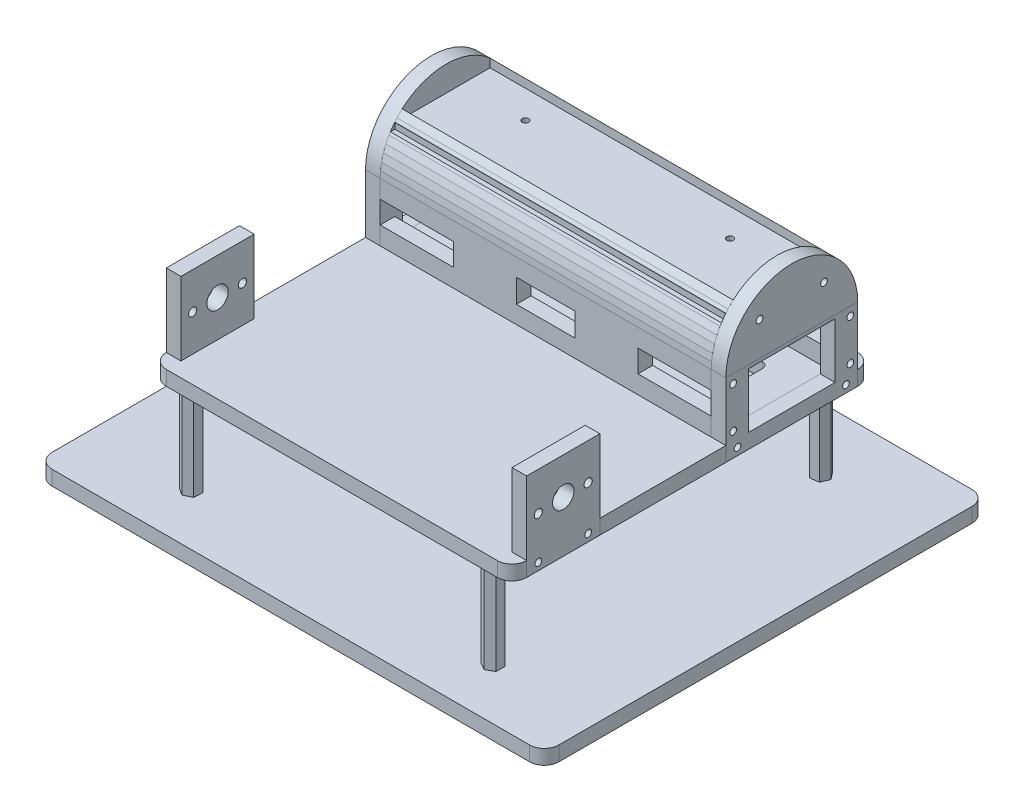
SolidWorks part; units mm, degrees
material "ABS"
ref_plane "Plano frontal" through (0, 0, 0) normal (0, 0, 1) x (1, 0, 0)
ref_plane "Plano superior" through (0, 0, 0) normal (0, 1, 0) x (1, 0, 0)
ref_plane "Plano direito" through (0, 0, 0) normal (1, 0, 0) x (0, 0, -1)
sketch "Esboço1" plane through (0, 0, 0) normal (0, 1, 0) x (1, 0, 0)
  line L1 (-20.6889, 116.4867) -> (92.3111, 116.4867)
  line L2 (-25.6889, 111.4867) -> (-25.6889, -1.5133)
  line L3 (-20.6889, -6.5133) -> (92.3111, -6.5133)
  line L4 (97.3111, 111.4867) -> (97.3111, -1.5133)
  arc A0 (92.3111, -6.5133) -> (97.3111, -1.5133) centre (92.3111, -1.5133) ccw
  arc A1 (-20.6889, -6.5133) -> (-25.6889, -1.5133) centre (-20.6889, -1.5133) cw
  arc A2 (97.3111, 111.4867) -> (92.3111, 116.4867) centre (92.3111, 111.4867) ccw
  arc A3 (-25.6889, 111.4867) -> (-20.6889, 116.4867) centre (-20.6889, 111.4867) cw
  dimension "D1" = 5
extrude "Ressalto-extrusão1" add sketch "Esboço1" along normal blind 5
sketch "Esboço2" plane through (0, 5, 0) normal (0, 1, 0) x (1, 0, 0)
  line L0 (97.3111, -1.5133) -> (97.3111, 111.4867) construction
  line L1 (97.3111, -1.5133) -> (92.3111, -1.5133)
  line L2 (97.3111, -1.5133) -> (97.3111, 23.4867)
  line L3 (97.3111, 23.4867) -> (92.3111, 23.4867)
  line L4 (92.3111, -1.5133) -> (92.3111, 23.4867)
  line L5 (-20.6889, -6.5133) -> (92.3111, -6.5133) construction
  line L6 (-25.6889, 111.4867) -> (-25.6889, -1.5133) construction
  line L7 (-25.6889, -1.5133) -> (-20.6889, -1.5133)
  line L8 (-25.6889, -1.5133) -> (-25.6889, 23.4867)
  line L9 (-25.6889, 23.4867) -> (-20.6889, 23.4867)
  line L10 (-20.6889, -1.5133) -> (-20.6889, 23.4867)
  dimension "D1" = 5
  dimension "D2" = 5
extrude "Corte-extrusão1" cut sketch "Esboço2" against normal blind 5
sketch "Esboço7" plane through (0, 5, 0) normal (0, 1, 0) x (1, 0, 0)
  line L0 (92.3111, 116.4867) -> (-20.6889, 116.4867) construction
  line L1 (97.3111, 111.4867) -> (92.3111, 111.4867)
  line L2 (97.3111, 111.4867) -> (97.3111, 66.4867)
  line L3 (97.3111, 66.4867) -> (92.3111, 66.4867)
  line L4 (92.3111, 111.4867) -> (92.3111, 66.4867)
  line L5 (-25.6889, 111.4867) -> (-20.6889, 111.4867)
  line L6 (-25.6889, 111.4867) -> (-25.6889, 66.4867)
  line L7 (-25.6889, 66.4867) -> (-20.6889, 66.4867)
  line L8 (-20.6889, 111.4867) -> (-20.6889, 66.4867)
  dimension "D1" = 5
  dimension "D2" = 5
extrude "Corte-extrusão4" cut sketch "Esboço7" against normal blind 5
sketch "Esboço11" plane through (0, 5, 0) normal (0, 1, 0) x (1, 0, 0)
  line L1 (97.3111, 111.4867) -> (92.3111, 111.4867)
  line L2 (97.3111, 111.4867) -> (97.3111, 66.4867)
  line L3 (97.3111, 66.4867) -> (92.3111, 66.4867)
  line L4 (92.3111, 111.4867) -> (92.3111, 66.4867)
  line L5 (-20.6889, 66.4867) -> (-25.6889, 66.4867)
  line L6 (-20.6889, 66.4867) -> (-20.6889, 111.4867)
  line L7 (-20.6889, 111.4867) -> (-25.6889, 111.4867)
  line L8 (-25.6889, 66.4867) -> (-25.6889, 111.4867)
extrude "Ressalto-extrusão4" add sketch "Esboço11" along normal blind 20 and the other way blind 5 separate body
sketch "Esboço12" plane through (97.3111, 0, 0) normal (1, 0, 0) x (0, 0, -1)
  line L4 (111.4867, 0) -> (111.4867, 25)
  line L5 (111.4867, 25) -> (66.4867, 25)
  line L6 (66.4867, 25) -> (66.4867, 0)
  line L7 (66.4867, 0) -> (111.4867, 0)
  line L9 (111.4867, 25) -> (66.4867, 25)
  arc A0 (66.4867, 25) -> (111.4867, 25) centre (88.9867, 25) cw
  dimension "D1" = 0
extrude "Ressalto-extrusão5" add sketch "Esboço12" against normal blind 5 separate body
sketch "Esboço14" plane through (-25.6889, 0, 0) normal (-1, 0, 0) x (0, 0, 1)
  line L4 (-66.4867, 0) -> (-66.4867, 25)
  line L5 (-66.4867, 25) -> (-111.4867, 25)
  line L6 (-111.4867, 25) -> (-111.4867, 0)
  line L7 (-111.4867, 0) -> (-66.4867, 0)
  line L9 (-66.4867, 25) -> (-111.4867, 25)
  arc A0 (-111.4867, 25) -> (-66.4867, 25) centre (-88.9867, 25) cw
  dimension "D1" = 0
extrude "Ressalto-extrusão6" add sketch "Esboço14" against normal blind 5 separate body
sketch "Esboço18" plane through (0, 5, 0) normal (0, 1, 0) x (1, 0, 0)
  line L0 (92.3111, 111.4867) -> (92.3111, 66.4867) construction
  line L1 (-20.6889, 111.4867) -> (92.3111, 111.4867)
  line L2 (-20.6889, 111.4867) -> (-20.6889, 106.4867)
  line L3 (-20.6889, 106.4867) -> (92.3111, 106.4867)
  line L4 (92.3111, 111.4867) -> (92.3111, 106.4867)
  line L6 (-20.6889, 66.4867) -> (92.3111, 66.4867)
  line L7 (-20.6889, 66.4867) -> (-20.6889, 71.4867)
  line L8 (-20.6889, 71.4867) -> (92.3111, 71.4867)
  line L9 (92.3111, 66.4867) -> (92.3111, 71.4867)
extrude "Ressalto-extrusão8" add sketch "Esboço18" along normal blind 20 separate body contours L8 L9 L6 L7 | L3 L4 L1 L2
sketch "Esboço19" plane through (-20.6889, 0, 0) normal (1, 0, 0) x (0, 0, -1)
  line L0 (71.4867, 25) -> (71.4867, 37)
  line L1 (71.4867, 37) -> (69.9878, 37)
  line L2 (69.9878, 37) -> (69.5, 36.2481)
  line L3 (69.5, 36.2481) -> (68.4357, 34.16)
  line L4 (68.4357, 34.16) -> (67.5984, 31.985)
  line L5 (67.5984, 31.985) -> (66.9429, 29.5079)
  line L6 (66.9429, 29.5079) -> (66.5974, 27.2295)
  line L7 (66.5974, 27.2295) -> (66.4867, 25)
  line L8 (66.4867, 25) -> (71.4867, 25)
  line L9 (111.4867, 25) -> (106.4867, 25)
  arc A0 (111.4867, 25) -> (66.4867, 25) centre (88.9867, 25) ccw construction
extrude "Ressalto-extrusão9" add sketch "Esboço19" along normal blind 113 separate body contours L0 L1 L2 L3 L4 L5 L6 L7 L8
sketch "Esboço21" plane through (-20.6889, 0, 0) normal (1, 0, 0) x (0, 0, -1)
  line L0 (111.4867, 25) -> (106.4867, 25)
  line L1 (111.4867, 25) -> (106.4867, 25) construction
  line L2 (106.4867, 25) -> (106.4867, 37)
  line L3 (106.4867, 37) -> (107.986, 37)
  line L4 (107.986, 37) -> (108.4724, 36.2497)
  line L5 (108.4724, 36.2497) -> (109.5436, 34.1467)
  line L6 (109.5436, 34.1467) -> (110.3792, 31.9722)
  line L7 (110.3792, 31.9722) -> (110.9976, 29.6659)
  line L8 (110.9976, 29.6659) -> (111.3632, 27.3541)
  line L9 (111.3632, 27.3541) -> (111.4867, 25)
  arc A0 (111.4867, 25) -> (66.4867, 25) centre (88.9867, 25) ccw construction
extrude "Ressalto-extrusão10" add sketch "Esboço21" along normal blind 113 separate body
sketch "Esboço23" plane through (-20.6889, 0, 0) normal (1, 0, 0) x (0, 0, -1)
  line L0 (106.4867, 37) -> (106.4867, 25) construction
  line L1 (71.4867, 38.9) -> (106.4867, 38.9)
  line L2 (71.4867, 38.9) -> (71.4867, 33.9)
  line L3 (71.4867, 33.9) -> (106.4867, 33.9)
  line L4 (106.4867, 38.9) -> (106.4867, 33.9)
  arc A0 (111.4867, 25) -> (66.4867, 25) centre (88.9867, 25) ccw construction
  point P7 (88.9867, 47.5)
  dimension "D1" = 8.6
  dimension "D2" = 0
extrude "Ressalto-extrusão12" add sketch "Esboço23" along normal blind 113 separate body
sketch "Esboço24" plane through (0, 0, -111.4867) normal (0, 0, -1) x (-1, 0, 0)
  line L0 (20.6889, 25) -> (20.6889, 5) construction
  line L1 (20.6889, 18.81) -> (-4.3111, 18.81)
  line L2 (20.6889, 18.81) -> (20.6889, 11.19)
  line L3 (20.6889, 11.19) -> (-4.3111, 11.19)
  line L4 (-4.3111, 18.81) -> (-4.3111, 11.19)
  line L6 (-92.3111, 5) -> (20.6889, 5) construction
  line L8 (-92.3111, 25) -> (20.6889, 25) construction
  line L9 (-92.3111, 0) -> (-92.3111, 25) construction
  line L10 (-92.3111, 18.81) -> (-67.3111, 18.81)
  line L11 (-92.3111, 18.81) -> (-92.3111, 11.19)
  line L12 (-92.3111, 11.19) -> (-67.3111, 11.19)
  line L13 (-67.3111, 18.81) -> (-67.3111, 11.19)
  dimension "D1" = 6.19
  dimension "D2" = 6.19
extrude "Corte-extrusão5" cut sketch "Esboço24" against normal blind 5
sketch "Esboço25" plane through (0, 0, -66.4867) normal (0, 0, 1) x (1, 0, 0)
  line L0 (-20.6889, 25) -> (-20.6889, 5) construction
  line L1 (-20.6889, 18.81) -> (4.3111, 18.81)
  line L2 (-20.6889, 18.81) -> (-20.6889, 11.19)
  line L3 (-20.6889, 11.19) -> (4.3111, 11.19)
  line L4 (4.3111, 18.81) -> (4.3111, 11.19)
  line L5 (-20.6889, 25) -> (92.3111, 25) construction
  line L6 (-20.6889, 5) -> (92.3111, 5) construction
  line L7 (92.3111, 0) -> (92.3111, 25) construction
  line L8 (92.3111, 18.81) -> (67.3111, 18.81)
  line L9 (92.3111, 18.81) -> (92.3111, 11.19)
  line L10 (92.3111, 11.19) -> (67.3111, 11.19)
  line L11 (67.3111, 18.81) -> (67.3111, 11.19)
  dimension "D1" = 6.19
  dimension "D2" = 6.19
extrude "Corte-extrusão6" cut sketch "Esboço25" against normal blind 5
sketch "Esboço26" plane through (-25.6889, 0, 0) normal (-1, 0, 0) x (0, 0, 1)
  line L0 (-111.4867, 0) -> (-66.4867, 0) construction
  line L1 (-111.4867, 5) -> (-111.4867, 0) construction
  line L2 (-66.4867, 0) -> (-66.4867, 5) construction
  line L3 (-111.4867, 0) -> (-111.4867, 25) construction
  line L4 (-66.4867, 0) -> (-66.4867, 25) construction
  circle A0 centre (-107.4867, 2.5) radius 1.15
  circle A1 centre (-70.4867, 2.5) radius 1.15
  circle A2 centre (-108.9867, 8) radius 1.15
  circle A3 centre (-68.9867, 8) radius 1.15
  circle A4 centre (-108.9867, 22) radius 1.15
  circle A5 centre (-68.9867, 22) radius 1.15
  circle A6 centre (-99.9867, 36.5) radius 1.15
  circle A7 centre (-77.9867, 36.5) radius 1.15
  arc A8 (-66.4867, 25) -> (-111.4867, 25) centre (-88.9867, 25) ccw construction
  point P10 (-66.4867, 2.5)
  point P30 (-88.9867, 47.5)
  dimension "D1" = 2.5
  dimension "D3" = 4
  dimension "D4" = 2.5
  dimension "D5" = 2.5
  dimension "D6" = 8
  dimension "D7" = 2.5
  dimension "D8" = 8
  dimension "D9" = 22
  dimension "D10" = 11
  dimension "D11" = 11
  dimension "D12" = 11.5
  dimension "D13" = 11.5
  dimension "D2" = 4
extrude "Corte-extrusão8" cut sketch "Esboço26" against normal blind 5
sketch "Esboço27" plane through (97.3111, 0, 0) normal (1, 0, 0) x (0, 0, -1)
  line L0 (66.4867, 0) -> (66.4867, 5) construction
  line L1 (111.4867, 5) -> (111.4867, 0) construction
  line L2 (66.4867, 0) -> (111.4867, 0) construction
  line L3 (66.4867, 0) -> (66.4867, 25) construction
  line L4 (111.4867, 0) -> (111.4867, 25) construction
  circle A0 centre (70.4867, 2.5) radius 1.15
  circle A1 centre (107.4867, 2.5) radius 1.15
  circle A2 centre (68.9867, 8) radius 1.15
  circle A3 centre (68.9867, 22) radius 1.15
  circle A4 centre (77.9867, 36.5) radius 1.15
  circle A5 centre (99.9867, 36.5) radius 1.15
  circle A6 centre (108.9867, 22) radius 1.15
  circle A7 centre (108.9867, 8) radius 1.15
  arc A8 (111.4867, 25) -> (66.4867, 25) centre (88.9867, 25) ccw construction
  point P19 (66.4867, 2.5)
  point P31 (88.9867, 47.5)
  dimension "D1" = 4
  dimension "D2" = 4
  dimension "D4" = 2.5
  dimension "D5" = 2.5
  dimension "D7" = 2.5
  dimension "D9" = 22
  dimension "D10" = 22
  dimension "D11" = 2.5
  dimension "D12" = 2.5
  dimension "D13" = 11
  dimension "D14" = 11
  dimension "D15" = 11.5
  dimension "D16" = 11.5
  dimension "D3" = 2.5
  dimension "D6" = 8
  dimension "D8" = 8
extrude "Corte-extrusão9" cut sketch "Esboço27" against normal blind 5
sketch "Esboço28" plane through (0, 0, -66.4867) normal (0, 0, 1) x (1, 0, 0)
  line L0 (-20.6889, 0) -> (-20.6889, 25) construction
  line L1 (25.8111, 11) -> (45.8111, 11)
  line L2 (25.8111, 11) -> (25.8111, 19)
  line L3 (25.8111, 19) -> (45.8111, 19)
  line L4 (45.8111, 11) -> (45.8111, 19)
  line L6 (92.3111, 0) -> (92.3111, 25) construction
  line L7 (-20.6889, 5) -> (92.3111, 5) construction
  line L9 (92.3111, 25) -> (-20.6889, 25) construction
  point P8 (92.3111, 12.5)
  dimension "D1" = 46.5
  dimension "D2" = 46.5
  dimension "D3" = 6
  dimension "D4" = 6
extrude "Corte-extrusão10" cut sketch "Esboço28" against normal blind 5
sketch "Esboço30" plane through (0, 5, 0) normal (0, 1, 0) x (1, 0, 0)
  line L1 (92.3111, -1.5133) -> (97.3111, -1.5133)
  line L2 (92.3111, -1.5133) -> (92.3111, 23.4867)
  line L3 (92.3111, 23.4867) -> (97.3111, 23.4867)
  line L4 (97.3111, -1.5133) -> (97.3111, 23.4867)
  line L5 (-20.6889, -1.5133) -> (-25.6889, -1.5133)
  line L6 (-20.6889, -1.5133) -> (-20.6889, 23.4867)
  line L7 (-20.6889, 23.4867) -> (-25.6889, 23.4867)
  line L8 (-25.6889, -1.5133) -> (-25.6889, 23.4867)
extrude "Ressalto-extrusão13" add sketch "Esboço30" along normal blind 25 and the other way blind 5 separate body
sketch "Esboço31" plane through (-25.6889, 0, 0) normal (-1, 0, 0) x (0, 0, 1)
  line L0 (1.5133, 5) -> (1.5133, 0) construction
  line L2 (-23.4867, 0) -> (1.5133, 0) construction
  line L3 (-23.4867, 0) -> (-23.4867, 5) construction
  line L4 (-23.4867, 30) -> (1.5133, 30) construction
  line L5 (1.5133, 0) -> (1.5133, 30) construction
  circle A0 centre (-19.4867, 2.5) radius 1.15
  circle A1 centre (-2.4867, 2.5) radius 1.15
  circle A2 centre (-10.9867, 17.5) radius 3.65
  circle A3 centre (-19.4867, 17.5) radius 1.4
  circle A4 centre (-2.4867, 17.5) radius 1.4
  point P16 (-23.4867, 2.5)
  dimension "D1" = 4
  dimension "D2" = 2.5
  dimension "D3" = 2.5
  dimension "D4" = 4
  dimension "D5" = 12.5
  dimension "D6" = 12.5
  dimension "D7" = 12.5
  dimension "D8" = 8.5
  dimension "D9" = 12.5
  dimension "D10" = 8.5
extrude "Corte-extrusão14" cut sketch "Esboço31" against normal blind 5 contours A4 | A1 | A0 | A3 | A2
sketch "Esboço32" plane through (97.3111, 0, 0) normal (1, 0, 0) x (0, 0, -1)
  line L0 (-1.5133, 30) -> (23.4867, 30) construction
  line L1 (-1.5133, 0) -> (-1.5133, 30) construction
  line L2 (-1.5133, 5) -> (-1.5133, 0) construction
  line L3 (-1.5133, 0) -> (23.4867, 0) construction
  line L4 (23.4867, 0) -> (23.4867, 5) construction
  circle A0 centre (2.4867, 2.5) radius 1.15
  circle A1 centre (19.4867, 2.5) radius 1.15
  circle A2 centre (10.9867, 17.5) radius 3.65
  circle A3 centre (2.4867, 16.9075) radius 1.4
  circle A4 centre (19.4867, 17.5) radius 1.4
  dimension "D1" = 12.5
  dimension "D2" = 12.5
  dimension "D3" = 13.0925
  dimension "D4" = 12.5
  dimension "D5" = 8.5
  dimension "D6" = 8.5
  dimension "D7" = 4
  dimension "D8" = 2.5
  dimension "D9" = 4
  dimension "D10" = 2.5
extrude "Corte-extrusão15" cut sketch "Esboço32" against normal blind 5 contours A0 | A1 | A4 | A3 | A2
sketch "Esboço33" plane through (0, 0, 0) normal (0, -1, 0) x (1, 0, 0)
  line L0 (92.3111, -116.4867) -> (-20.6889, -116.4867) construction
  line L1 (78.8111, -97.4867) -> (-7.1889, -97.4867)
  line L2 (80.8111, -95.4867) -> (80.8111, -83.4867)
  line L3 (78.8111, -81.4867) -> (-7.1889, -81.4867)
  line L4 (-9.1889, -95.4867) -> (-9.1889, -83.4867)
  line L8 (97.3111, -66.4867) -> (97.3111, -111.4867) construction
  line L9 (-25.6889, -111.4867) -> (-25.6889, -66.4867) construction
  arc A0 (-9.1889, -95.4867) -> (-7.1889, -97.4867) centre (-7.1889, -95.4867) ccw
  arc A1 (-7.1889, -81.4867) -> (-9.1889, -83.4867) centre (-7.1889, -83.4867) ccw
  arc A2 (78.8111, -81.4867) -> (80.8111, -83.4867) centre (78.8111, -83.4867) cw
  arc A3 (78.8111, -97.4867) -> (80.8111, -95.4867) centre (78.8111, -95.4867) ccw
  dimension "D4" = 2
  dimension "D1" = 19
  dimension "D2" = 16.5
  dimension "D3" = 16.5
extrude "Corte-extrusão16" cut sketch "Esboço33" against normal blind 5
sketch "Esboço35" plane through (97.3111, 0, 0) normal (1, 0, 0) x (0, 0, -1)
  line L0 (66.4867, 0) -> (111.4867, 0) construction
  line L1 (74.1917, 23.85) -> (103.7817, 23.85)
  line L2 (74.1917, 23.85) -> (74.1917, 5)
  line L3 (74.1917, 5) -> (103.7817, 5)
  line L4 (103.7817, 23.85) -> (103.7817, 5)
  line L5 (66.4867, 0) -> (66.4867, 25) construction
  line L8 (111.4867, 0) -> (111.4867, 25) construction
  dimension "D1" = 5
  dimension "D2" = 7.705
  dimension "D3" = 7.705
extrude "Corte-extrusão18" cut sketch "Esboço35" against normal blind 5
sketch "Esboço36" plane through (-25.6889, 0, 0) normal (-1, 0, 0) x (0, 0, 1)
  line L0 (-111.4867, 0) -> (-66.4867, 0) construction
  line L1 (-74.1917, 5) -> (-103.7817, 5)
  line L2 (-74.1917, 5) -> (-74.1917, 23.85)
  line L3 (-74.1917, 23.85) -> (-103.7817, 23.85)
  line L4 (-103.7817, 5) -> (-103.7817, 23.85)
  line L5 (-66.4867, 0) -> (-66.4867, 25) construction
  line L6 (-111.4867, 0) -> (-111.4867, 25) construction
  dimension "D1" = 5
  dimension "D2" = 7.705
  dimension "D3" = 7.705
extrude "Corte-extrusão19" cut sketch "Esboço36" against normal blind 5
sketch "Esboço37" plane through (0, 38.9, 0) normal (0, 1, 0) x (1, 0, 0)
  line L0 (92.3111, 106.4867) -> (-20.6889, 106.4867) construction
  line L1 (-20.6889, 106.4867) -> (-20.6889, 71.4867) construction
  line L2 (92.3111, 106.4867) -> (92.3111, 71.4867) construction
  circle A0 centre (70.7361, 94.4867) radius 1.1
  circle A1 centre (0.8861, 94.4867) radius 1.1
  dimension "D1" = 69.85
  dimension "D2" = 21.575
  dimension "D4" = 12
  dimension "D3" = 21.575
extrude "Corte-extrusão20" cut sketch "Esboço37" against normal blind 5
sketch "Esboço38" plane through (0, 0, 0) normal (0, -1, 0) x (-1, 0, 0)
  line L0 (-97.3111, -1.5133) -> (-97.3111, 23.4867) construction
  line L1 (-87.3111, -0.0133) -> (-89.9091, -1.5133)
  line L2 (-89.9091, -1.5133) -> (-89.9091, -4.5133)
  line L3 (-89.9091, -4.5133) -> (-87.3111, -6.0133)
  line L4 (-87.3111, -6.0133) -> (-84.713, -4.5133)
  line L5 (-84.713, -4.5133) -> (-84.713, -1.5133)
  line L6 (-84.713, -1.5133) -> (-87.3111, -0.0133)
  line L7 (20.6889, -6.5133) -> (-92.3111, -6.5133) construction
  line L8 (25.6889, 23.4867) -> (25.6889, -1.5133) construction
  line L9 (13.0097, -1.6637) -> (13.1805, -4.6589)
  line L10 (13.1805, -4.6589) -> (15.8598, -6.0085)
  line L11 (15.8598, -6.0085) -> (18.3682, -4.363)
  line L12 (18.3682, -4.363) -> (18.1974, -1.3678)
  line L13 (18.1974, -1.3678) -> (15.5181, -0.0182)
  line L14 (15.5181, -0.0182) -> (13.0097, -1.6637)
  line L15 (-92.3111, 116.4867) -> (20.6889, 116.4867) construction
  line L16 (13.2344, 110.7116) -> (12.9679, 107.7235)
  line L17 (12.9679, 107.7235) -> (15.4224, 105.9985)
  line L18 (15.4224, 105.9985) -> (18.1435, 107.2617)
  line L19 (18.1435, 107.2617) -> (18.41, 110.2499)
  line L20 (18.41, 110.2499) -> (15.9555, 111.9748)
  line L21 (15.9555, 111.9748) -> (13.2344, 110.7116)
  line L22 (25.6889, 111.4867) -> (25.6889, 66.4867) construction
  line L23 (-97.3111, 66.4867) -> (-97.3111, 111.4867) construction
  line L24 (-88.4409, 111.7658) -> (-90.2828, 109.3977)
  line L25 (-90.2828, 109.3977) -> (-89.1529, 106.6186)
  line L26 (-89.1529, 106.6186) -> (-86.1812, 106.2076)
  line L27 (-86.1812, 106.2076) -> (-84.3393, 108.5756)
  line L28 (-84.3393, 108.5756) -> (-85.4692, 111.3547)
  line L29 (-85.4692, 111.3547) -> (-88.4409, 111.7658)
  circle A0 centre (-87.3111, -3.0133) radius 3 construction
  circle A1 centre (15.6889, -3.0133) radius 3 construction
  circle A2 centre (15.6889, 108.9867) radius 3 construction
  circle A3 centre (-87.3111, 108.9867) radius 3 construction
  dimension "D1" = 10
  dimension "D2" = 3.5
  dimension "D3" = 3.5
  dimension "D4" = 10
  dimension "D5" = 7.5
  dimension "D6" = 10
  dimension "D7" = 7.5
  dimension "D8" = 10
extrude "Ressalto-extrusão14" add sketch "Esboço38" along normal blind 30 separate body
sketch "Esboço39" plane through (0, -30, 0) normal (0, -1, 0) x (1, 0, 0)
  line L0 (-20.6889, 6.5133) -> (92.3111, 6.5133) construction
  line L1 (-45.6889, -130.4867) -> (117.3111, -130.4867)
  line L2 (-50.6889, -125.4867) -> (-50.6889, 15.5133)
  line L3 (-45.6889, 20.5133) -> (117.3111, 20.5133)
  line L4 (122.3111, -125.4867) -> (122.3111, 15.5133)
  line L5 (92.3111, -116.4867) -> (-20.6889, -116.4867) construction
  line L6 (97.3111, 1.5133) -> (97.3111, -23.4867) construction
  line L7 (-25.6889, -66.4867) -> (-25.6889, -23.4867) construction
  arc A0 (122.3111, 15.5133) -> (117.3111, 20.5133) centre (117.3111, 15.5133) ccw
  arc A1 (122.3111, -125.4867) -> (117.3111, -130.4867) centre (117.3111, -125.4867) cw
  arc A2 (-45.6889, 20.5133) -> (-50.6889, 15.5133) centre (-45.6889, 15.5133) ccw
  arc A3 (-50.6889, -125.4867) -> (-45.6889, -130.4867) centre (-45.6889, -125.4867) ccw
  point P10 (97.3111, -10.9867)
  dimension "D5" = 5
  dimension "D1" = 14
  dimension "D2" = 14
  dimension "D3" = 25
  dimension "D4" = 25
extrude "Ressalto-extrusão15" add sketch "Esboço39" along normal blind 5 separate body
sketch "Esboço41" plane through (0, 0, -111.4867) normal (0, 0, -1) x (-1, 0, 0)
  line L0 (20.6889, 0) -> (20.6889, 25) construction
  line L1 (-92.3111, 0) -> (-92.3111, 25) construction
  line L2 (-92.3111, 5) -> (20.6889, 5) construction
  circle A0 centre (-17.1411, 20) radius 1.6
  circle A1 centre (-54.4811, 20) radius 1.6
  dimension "D1" = 37.83
  dimension "D2" = 37.83
  dimension "D3" = 37.34
  dimension "D4" = 15
extrude "Corte-extrusão21" cut sketch "Esboço41" against normal blind 5
sketch "Esboço42" plane through (-20.6889, 0, 0) normal (1, 0, 0) x (0, 0, -1)
  line L0 (71.4867, 38.9) -> (71.4867, 39.0928)
  line L1 (71.4867, 38.9) -> (73.9867, 38.9)
  line L2 (73.9867, 38.9) -> (73.9867, 41.7705)
  line L3 (73.9867, 41.7705) -> (72.2162, 40)
  line L4 (72.2162, 40) -> (71.4867, 39.0928)
  arc A0 (111.4867, 25) -> (66.4867, 25) centre (88.9867, 25) ccw construction
extrude "Ressalto-extrusão16" add sketch "Esboço42" along normal blind 113 separate body
sketch "Esboço43" plane through (-20.6889, 0, 0) normal (1, 0, 0) x (0, 0, -1)
  line L0 (106.4867, 38.9) -> (103.9867, 38.9)
  line L2 (106.4867, 38.9) -> (71.4867, 38.9) construction
  line L3 (103.9867, 38.9) -> (103.9867, 41.7705)
  line L4 (103.9867, 41.7705) -> (105.7009, 40.0626)
  line L5 (105.7009, 40.0626) -> (106.4867, 39.0868)
  line L6 (106.4867, 39.0868) -> (106.4867, 38.9)
  arc A0 (111.4867, 25) -> (66.4867, 25) centre (88.9867, 25) ccw construction
extrude "Ressalto-extrusão17" add sketch "Esboço43" along normal blind 113 separate body
